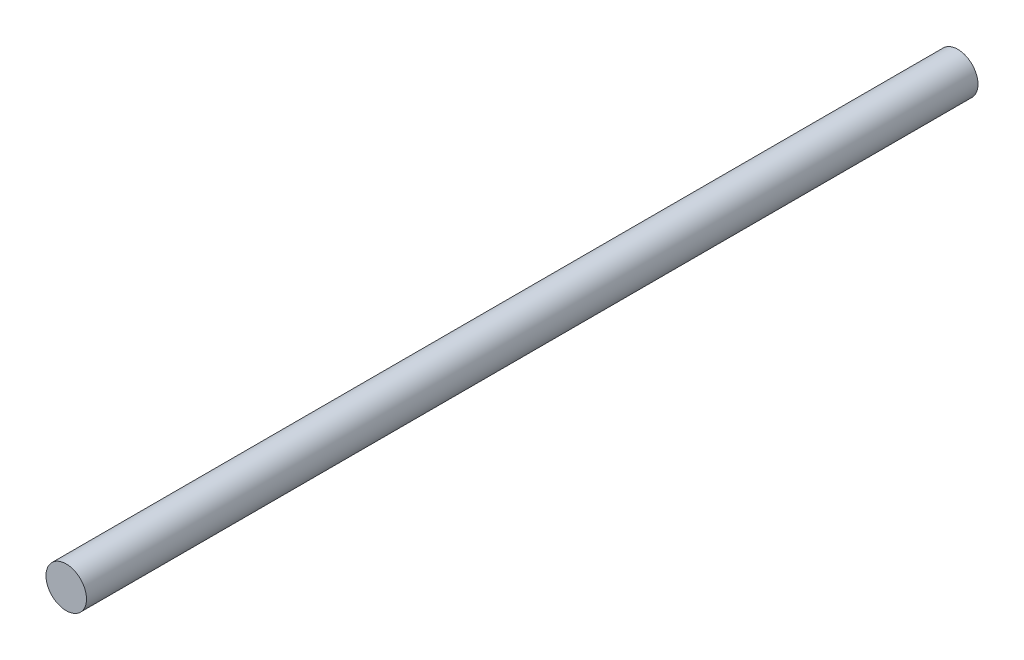
SolidWorks part; units mm, degrees
ref_plane "Front Plane" through (0, 0, 0) normal (0, 0, 1) x (1, 0, 0)
ref_plane "Top Plane" through (0, 0, 0) normal (0, 1, 0) x (1, 0, 0)
ref_plane "Right Plane" through (0, 0, 0) normal (1, 0, 0) x (0, 0, -1)
sketch "Sketch1" plane through (0, 0, 0) normal (0, 0, 1) x (1, 0, 0)
  circle A0 centre (0, 0) radius 2.5
  dimension "D1" = 5
extrude "Boss-Extrude1" add sketch "Sketch1" along normal blind 110
